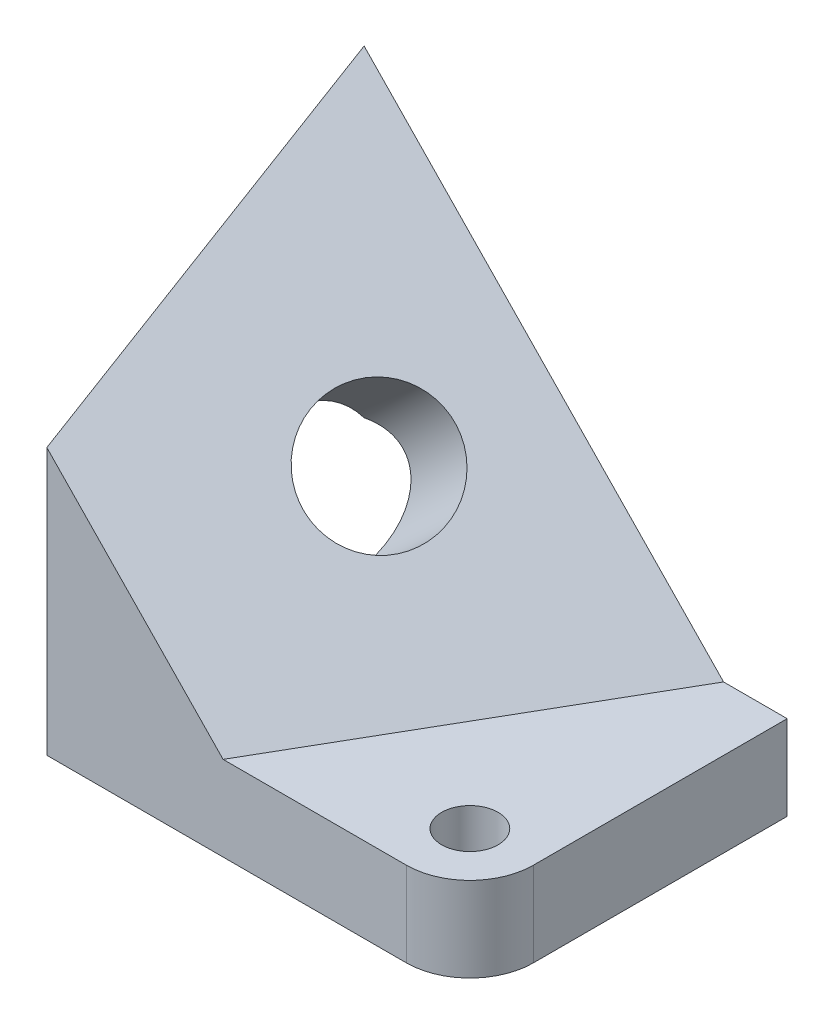
SolidWorks part; units mm, degrees
ref_plane "前视基准面" through (0, 0, 0) normal (0, 0, 1) x (1, 0, 0)
ref_plane "上视基准面" through (0, 0, 0) normal (0, 1, 0) x (1, 0, 0)
ref_plane "右视基准面" through (0, 0, 0) normal (1, 0, 0) x (0, 0, -1)
other "Configuration Table"
sketch "草图1" plane through (0, 0, 0) normal (0, 1, 0) x (1, 0, 0)
  line L1 (-30, 22.5) -> (30, 22.5)
  line L2 (-30, 22.5) -> (-30, -22.5)
  line L3 (-30, -22.5) -> (21, -22.5)
  line L4 (30, 22.5) -> (30, -13.5)
  line L5 (-30, 22.5) -> (30, -22.5) construction
  line L6 (-30, -22.5) -> (30, 22.5) construction
  arc A0 (21, -22.5) -> (30, -13.5) centre (21, -13.5) ccw
  circle A1 centre (21, -13.5) radius 4
  point P0 (0, 0)
  dimension "D1" = 9
  dimension "D4" = 8
  dimension "D2" = 60
  dimension "D3" = 45
extrude "凸台-拉伸1" add sketch "草图1" along normal blind 12
sketch "草图4" plane through (0, 12, 0) normal (0, 1, 0) x (1, 0, 0)
  line L0 (-5, -22.5) -> (20.9808, 22.5)
  line L1 (-30, -22.5) -> (21, -22.5) construction
  line L2 (30, 22.5) -> (-30, 22.5) construction
  line L3 (30, -13.5) -> (30, 22.5) construction
  dimension "D1" = 60
  dimension "D2" = 35
ref_plane "基准面1" through (8.6339, 8.3655, 4.9848) normal (-0.6634, -0.6428, -0.383) x (0.5, 0, -0.866)
sketch "草图5" plane through (0, 12, 0) normal (0, 1, 0) x (1, 0, 0)
  line L0 (-5, -22.5) -> (20.9808, 22.5) construction
  line L1 (-5, -22.5) -> (20.9808, 22.5)
  line L2 (-30, -22.5) -> (21, -22.5) construction
  line L3 (-30, 22.5) -> (-30, -22.5) construction
  line L4 (30, 22.5) -> (-30, 22.5) construction
  line L5 (-30, -22.5) -> (-5, -22.5)
  line L6 (-30, 22.5) -> (-30, -22.5)
  line L7 (20.9808, 22.5) -> (-30, 22.5)
extrude "凸台-拉伸2" add sketch "草图5" along normal blind 55
sketch "草图6" plane through (8.6339, 8.3655, 4.9848) normal (-0.6634, -0.6428, -0.383) x (0.5, 0, -0.866)
  line L0 (-21.9856, -4.7445) -> (29.976, -4.7445) construction
  line L1 (-21.9856, -4.7445) -> (29.976, -4.7445)
  line L2 (-21.9856, -4.7445) -> (-55.1845, -73.7854)
  line L3 (-55.1845, -73.7854) -> (18.6008, -97.1201)
  line L4 (18.6008, -97.1201) -> (46.8613, -7.7592)
  line L5 (46.8613, -7.7592) -> (29.976, -4.7445)
extrude "切除-拉伸1" cut sketch "草图6" against normal blind 50
ref_plane "基准面2" through (0, 0, 13.5) normal (0, 0, 1) x (0, -1, 0)
sketch "草图7" plane through (0, 0, 13.5) normal (0, 0, 1) x (0, -1, 0)
  line L0 (-12, 21) -> (-62, 21) construction
  line L1 (-12, 21) -> (0, 21) construction
  dimension "D1" = 50
ref_plane "基准面3" through (-0.5957, 0, 1.0317) normal (0.5, 0, -0.866) x (0, 1, 0)
sketch "草图8" plane through (-0.5957, 0, 1.0317) normal (0.5, 0, -0.866) x (0, 1, 0)
  line L0 (32.5747, -10.1312) -> (62, 24.9365) construction
  line L1 (64.6167, -37.2308) -> (12, 6.9199) construction
sketch "草图9" plane through (8.6339, 8.3655, 4.9848) normal (0.6634, 0.6428, 0.383) x (0.2751, 0.2665, -0.9237)
  circle A0 centre (9.8309, 29.9144) radius 9
  dimension "D1" = 18
extrude "切除-拉伸2" cut sketch "草图9" against normal through all
